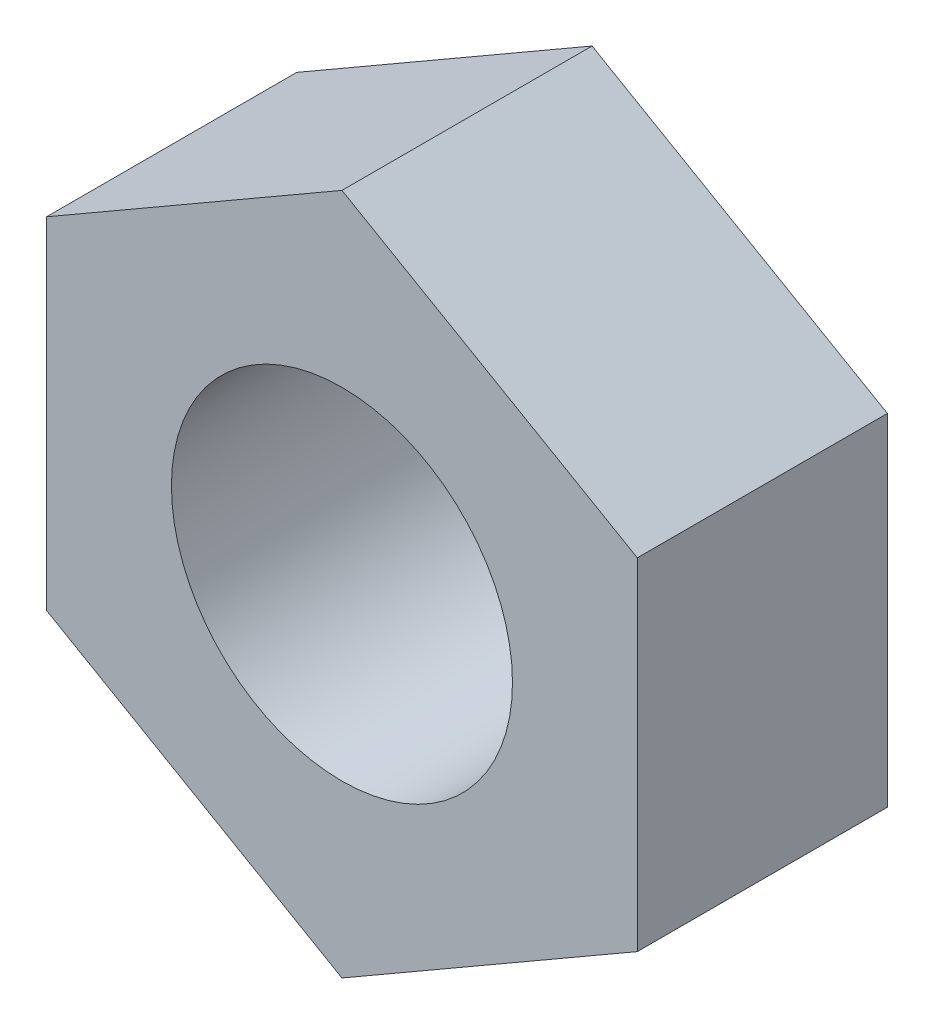
SolidWorks part; units mm, degrees
ref_plane "Front Plane" through (0, 0, 0) normal (0, 0, 1) x (1, 0, 0)
ref_plane "Top Plane" through (0, 0, 0) normal (0, 1, 0) x (1, 0, 0)
ref_plane "Right Plane" through (0, 0, 0) normal (1, 0, 0) x (0, 0, -1)
sketch "Sketch1" plane through (0, 0, 0) normal (0, 0, 1) x (1, 0, 0)
  line L0 (0, 0) -> (0, 3) construction
  line L2 (0, 3) -> (-2.5981, 1.5)
  line L3 (-2.5981, 1.5) -> (-2.5981, -1.5)
  line L4 (-2.5981, -1.5) -> (0, -3)
  line L5 (0, -3) -> (2.5981, -1.5)
  line L6 (2.5981, -1.5) -> (2.5981, 1.5)
  line L7 (2.5981, 1.5) -> (0, 3)
  circle A0 centre (0, 0) radius 1.5
  circle A1 centre (0, 0) radius 2.5981 construction
  dimension "D1" = 3
  dimension "D2" = 3
extrude "Boss-Extrude1" add sketch "Sketch1" along normal blind 2.2
